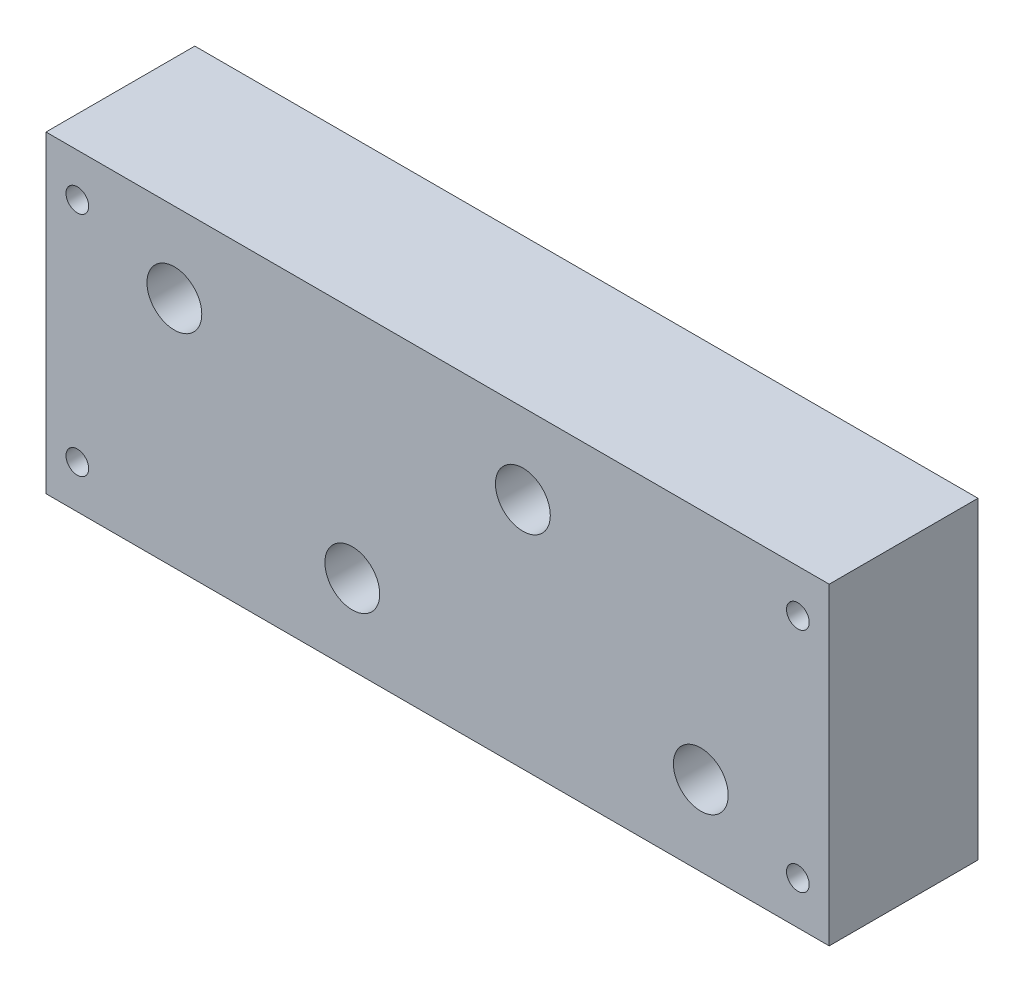
SolidWorks part; units mm, degrees
material "ABS PC"
ref_plane "Front Plane" through (0, 0, 0) normal (0, 0, 1) x (1, 0, 0)
ref_plane "Top Plane" through (0, 0, 0) normal (0, 1, 0) x (1, 0, 0)
ref_plane "Right Plane" through (0, 0, 0) normal (1, 0, 0) x (0, 0, -1)
sketch "Sketch1" plane through (0, 0, 0) normal (0, 0, 1) x (1, 0, 0)
  line L1 (-33.75, 21.5625) -> (66.25, 21.5625)
  line L2 (-33.75, 21.5625) -> (-33.75, -18.4375)
  line L3 (-33.75, -18.4375) -> (66.25, -18.4375)
  line L4 (66.25, 21.5625) -> (66.25, -18.4375)
  dimension "D1" = 100
  dimension "D2" = 40
extrude "Boss-Extrude1" add sketch "Sketch1" along normal blind 38
sketch "Sketch2" plane through (0, 0, 0) normal (0, 0, -1) x (-1, 0, 0)
  line L0 (-66.25, -18.4375) -> (-66.25, 21.5625) construction
  line L1 (-58.25, 18.5625) -> (-18.75, 18.5625)
  line L2 (-58.25, 18.5625) -> (-58.25, -15.4375)
  line L3 (-58.25, -15.4375) -> (-18.75, -15.4375)
  line L4 (-18.75, 18.5625) -> (-18.75, -15.4375)
  line L5 (-13.75, 18.5625) -> (25.75, 18.5625)
  line L6 (-13.75, 18.5625) -> (-13.75, -15.4375)
  line L7 (-13.75, -15.4375) -> (25.75, -15.4375)
  line L8 (25.75, 18.5625) -> (25.75, -15.4375)
  line L9 (33.75, 21.5625) -> (33.75, -18.4375) construction
  line L10 (-66.25, 21.5625) -> (33.75, 21.5625) construction
  line L11 (33.75, -18.4375) -> (-66.25, -18.4375) construction
  dimension "D1" = 8
  dimension "D2" = 8
  dimension "D3" = 5
  dimension "D4" = 3
  dimension "D5" = 3
  dimension "D6" = 3
  dimension "D7" = 3
  dimension "D8" = 39.5
  dimension "D9" = 39.5
extrude "Cut-Extrude2" cut sketch "Sketch2" against normal blind 21 from offset 12 offset against normal yes
sketch "Sketch3" plane through (-3.3623, 0, 0) normal (0, 0, -1) x (-1, 0, 0)
  arc A0 (-55.6418, 7.0775) -> (16.2528, 4.0018) centre (-18.1567, 41.487) ccw construction
  arc A1 (-61.5934, 1.6143) -> (21.716, -1.9497) centre (-18.1567, 41.487) ccw
  arc A2 (-49.6903, 12.5407) -> (10.7896, 9.9533) centre (-18.1567, 41.487) ccw
  arc A3 (-49.6903, 12.5407) -> (-61.5934, 1.6143) centre (-55.6418, 7.0775) ccw
  arc A4 (21.716, -1.9497) -> (10.7896, 9.9533) centre (16.2528, 4.0018) ccw
  point P3 (-20.3315, -9.3502)
extrude "Cut-Extrude3" cut sketch "Sketch3" against normal blind 9 contours A2 A4 A1 A3
sketch "Sketch4" plane through (0, 0, 0) normal (0, 0, -1) x (-1, 0, 0)
  line L0 (-66.25, -18.4375) -> (-66.25, 21.5625) construction
  line L1 (33.75, 21.5625) -> (33.75, -18.4375) construction
  line L2 (-66.25, 21.5625) -> (33.75, 21.5625) construction
  line L3 (33.75, -18.4375) -> (-66.25, -18.4375) construction
  circle A0 centre (-62.25, 16.0625) radius 1.45
  circle A1 centre (-62.25, -12.9375) radius 1.45
  circle A2 centre (29.75, 16.0625) radius 1.45
  circle A3 centre (29.75, -12.9375) radius 1.45
  point P8 (0, 0)
  dimension "D1" = 4
  dimension "D2" = 4
  dimension "D3" = 5.5
  dimension "D4" = 5.5
extrude "Cut-Extrude4" cut sketch "Sketch4" against normal up to next
sketch "Sketch5" plane through (0, 21.5625, 0) normal (0, 1, 0) x (1, 0, 0)
  line L0 (-33.75, -38) -> (-33.75, 0) construction
  line L1 (66.25, 0) -> (-33.75, 0)
  line L2 (66.25, 0) -> (66.25, -19)
  line L3 (66.25, -19) -> (-33.75, -19)
  line L4 (-33.75, 0) -> (-33.75, -19)
extrude "Cut-Extrude5" cut sketch "Sketch5" against normal through all
fillet "Fillet1" radius 0.5 8 edges at (18.75, 18.5625, 26) (58.25, 18.5625, 26) (58.25, -15.4375, 26) (18.75, -15.4375, 26) (13.75, -15.4375, 26) (13.75, 18.5625, 26) (-25.75, 18.5625, 26) (-25.75, -15.4375, 26)
sketch "Sketch8" plane through (0, 0, 33) normal (0, 0, -1) x (-1, 0, 0)
  line L8 (-18.25, -14.9375) -> (-18.25, 18.0625)
  line L9 (-19.25, 19.0625) -> (-57.75, 19.0625)
  line L10 (-58.75, 18.0625) -> (-58.75, -14.9375)
  line L11 (-57.75, -15.9375) -> (-19.25, -15.9375)
  line L12 (-18.25, -14.9375) -> (-18.25, 18.0625)
  line L13 (-19.25, 19.0625) -> (-57.75, 19.0625)
  line L14 (-58.75, 18.0625) -> (-58.75, -14.9375)
  line L15 (-57.75, -15.9375) -> (-19.25, -15.9375)
  arc A8 (-18.25, 18.0625) -> (-19.25, 19.0625) centre (-19.25, 18.0625) ccw
  arc A9 (-57.75, 19.0625) -> (-58.75, 18.0625) centre (-57.75, 18.0625) ccw
  arc A10 (-58.75, -14.9375) -> (-57.75, -15.9375) centre (-57.75, -14.9375) ccw
  arc A11 (-19.25, -15.9375) -> (-18.25, -14.9375) centre (-19.25, -14.9375) ccw
  arc A12 (-18.25, 18.0625) -> (-19.25, 19.0625) centre (-19.25, 18.0625) ccw
  arc A13 (-57.75, 19.0625) -> (-58.75, 18.0625) centre (-57.75, 18.0625) ccw
  arc A14 (-58.75, -14.9375) -> (-57.75, -15.9375) centre (-57.75, -14.9375) ccw
  arc A15 (-19.25, -15.9375) -> (-18.25, -14.9375) centre (-19.25, -14.9375) ccw
  dimension "D1" = 0.5
sketch "Sketch9" plane through (0, 0, 33) normal (0, 0, -1) x (-1, 0, 0)
  line L8 (-14.25, 18.0625) -> (-14.25, -14.9375)
  line L9 (-13.25, -15.9375) -> (25.25, -15.9375)
  line L10 (26.25, -14.9375) -> (26.25, 18.0625)
  line L11 (25.25, 19.0625) -> (-13.25, 19.0625)
  line L12 (-14.25, 18.0625) -> (-14.25, -14.9375)
  line L13 (-13.25, -15.9375) -> (25.25, -15.9375)
  line L14 (26.25, -14.9375) -> (26.25, 18.0625)
  line L15 (25.25, 19.0625) -> (-13.25, 19.0625)
  arc A8 (-14.25, -14.9375) -> (-13.25, -15.9375) centre (-13.25, -14.9375) ccw
  arc A9 (25.25, -15.9375) -> (26.25, -14.9375) centre (25.25, -14.9375) ccw
  arc A10 (26.25, 18.0625) -> (25.25, 19.0625) centre (25.25, 18.0625) ccw
  arc A11 (-13.25, 19.0625) -> (-14.25, 18.0625) centre (-13.25, 18.0625) ccw
  arc A12 (-14.25, -14.9375) -> (-13.25, -15.9375) centre (-13.25, -14.9375) ccw
  arc A13 (25.25, -15.9375) -> (26.25, -14.9375) centre (25.25, -14.9375) ccw
  arc A14 (26.25, 18.0625) -> (25.25, 19.0625) centre (25.25, 18.0625) ccw
  arc A15 (-13.25, 19.0625) -> (-14.25, 18.0625) centre (-13.25, 18.0625) ccw
  dimension "D1" = 0.5
sketch "Sketch10" plane through (0, 0, 33) normal (0, 0, -1) x (-1, 0, 0)
  line L0 (-13.9571, -15.6446) -> (25.9571, 18.7696) construction
  line L1 (-58.4571, -15.6446) -> (-18.5429, 18.7696) construction
  line L2 (-27.1396, 11.3575) -> (-18.5429, 18.7696) construction
  line L3 (-27.1396, 11.3575) -> (-27.1396, 18.5625) construction
  line L4 (-19.25, 18.5625) -> (-57.75, 18.5625) construction
  line L5 (-49.8604, -8.2325) -> (-49.8604, -15.4375) construction
  line L6 (-57.75, -15.4375) -> (-19.25, -15.4375) construction
  circle A0 centre (-49.8604, -8.2325) radius 3.5
  circle A1 centre (-27.1396, 11.3575) radius 3.5
  circle A2 centre (-5.3604, -8.2325) radius 3.5
  circle A3 centre (17.3604, 11.3575) radius 3.5
  arc A4 (-14.25, -14.9375) -> (-13.25, -15.9375) centre (-13.25, -14.9375) ccw construction
  arc A5 (26.25, 18.0625) -> (25.25, 19.0625) centre (25.25, 18.0625) ccw construction
  arc A6 (-58.75, -14.9375) -> (-57.75, -15.9375) centre (-57.75, -14.9375) ccw construction
  arc A7 (-18.25, 18.0625) -> (-19.25, 19.0625) centre (-19.25, 18.0625) ccw construction
  point P24 (0, 0)
  point P31 (0, 0)
  dimension "D1" = 30
  dimension "D2" = 30
  dimension "D3" = 7
extrude "Cut-Extrude11" cut sketch "Sketch10" against normal up to next
